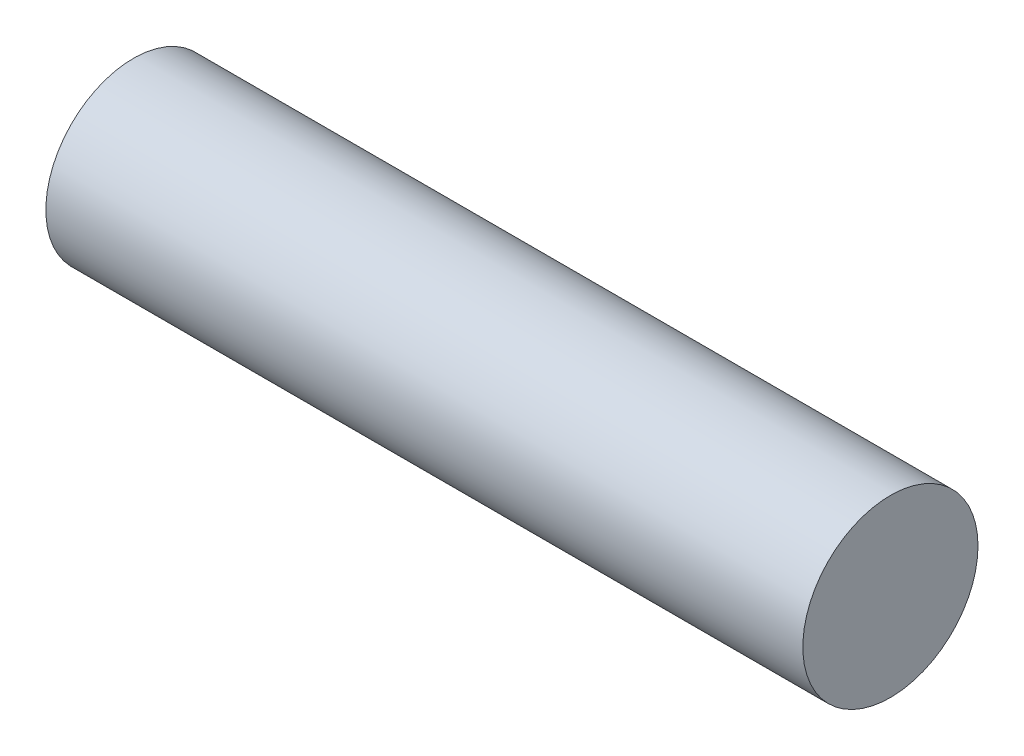
SolidWorks part; units mm, degrees
ref_plane "정면" through (0, 0, 0) normal (0, 0, 1) x (1, 0, 0)
ref_plane "윗면" through (0, 0, 0) normal (0, 1, 0) x (1, 0, 0)
ref_plane "우측면" through (0, 0, 0) normal (1, 0, 0) x (0, 0, -1)
sketch "Sketch1" plane through (0, 0, 0) normal (1, 0, 0) x (0, 0, -1)
  circle A0 centre (0, 0) radius 4.975
  dimension "D1" = 9.95
extrude "Boss-Extrude1" add sketch "Sketch1" along normal blind 43
